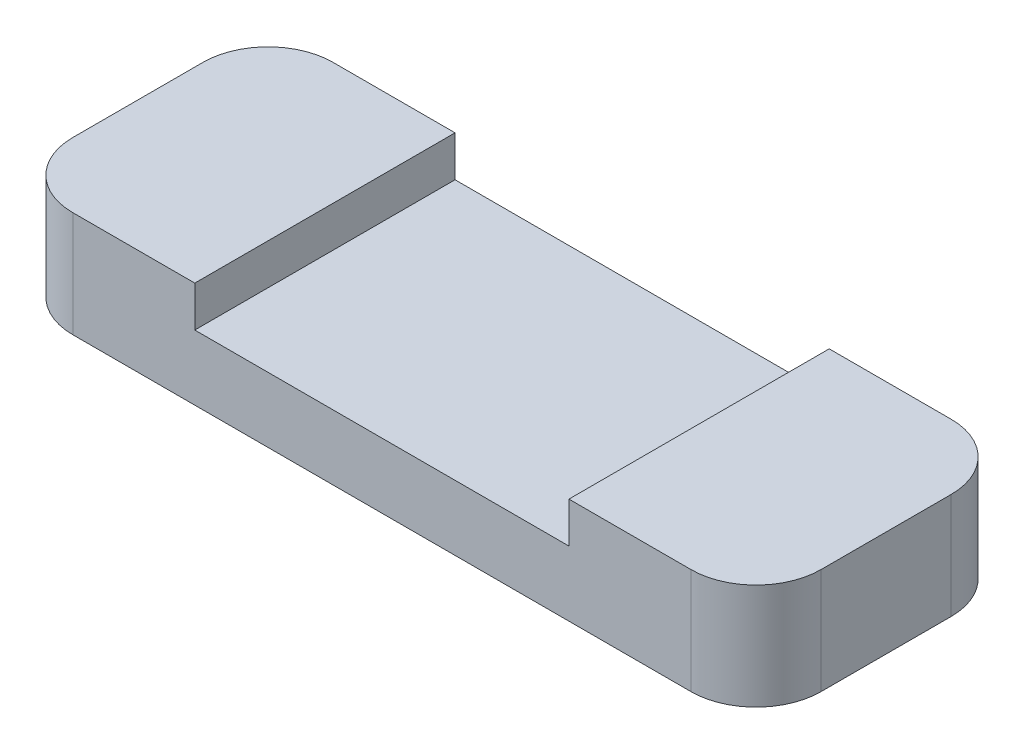
SolidWorks part; units mm, degrees
ref_plane "Alzado" through (0, 0, 0) normal (0, 0, 1) x (1, 0, 0)
ref_plane "Planta" through (0, 0, 0) normal (0, 1, 0) x (1, 0, 0)
ref_plane "Vista lateral" through (0, 0, 0) normal (1, 0, 0) x (0, 0, -1)
sketch "Croquis1" plane through (0, 0, 0) normal (0, 1, 0) x (1, 0, 0)
  line L1 (-19, 8) -> (19, 8)
  line L2 (-23, 4) -> (-23, -4)
  line L3 (-19, -8) -> (19, -8)
  line L4 (23, 4) -> (23, -4)
  line L5 (-23, 8) -> (23, -8) construction
  line L6 (-23, -8) -> (23, 8) construction
  arc A0 (19, 8) -> (23, 4) centre (19, 4) cw
  arc A1 (23, -4) -> (19, -8) centre (19, -4) cw
  arc A2 (-23, -4) -> (-19, -8) centre (-19, -4) ccw
  arc A3 (-19, 8) -> (-23, 4) centre (-19, 4) ccw
  point P0 (0, 0)
  dimension "D3" = 4
  dimension "D1" = 46
  dimension "D2" = 16
extrude "Saliente-Extruir1" add sketch "Croquis1" along normal blind 4.5 and the other way blind 2
sketch "Croquis2" plane through (0, 4.5, 0) normal (0, 1, 0) x (1, 0, 0)
  line L1 (-11.5, 10.1008) -> (11.5, 10.1008)
  line L2 (-11.5, 10.1008) -> (-11.5, -10.1008)
  line L3 (-11.5, -10.1008) -> (11.5, -10.1008)
  line L4 (11.5, 10.1008) -> (11.5, -10.1008)
  line L5 (-11.5, 10.1008) -> (11.5, -10.1008) construction
  line L6 (-11.5, -10.1008) -> (11.5, 10.1008) construction
  point P0 (0, 0)
  dimension "D1" = 23
extrude "Cortar-Extruir1" cut sketch "Croquis2" against normal blind 2.5
